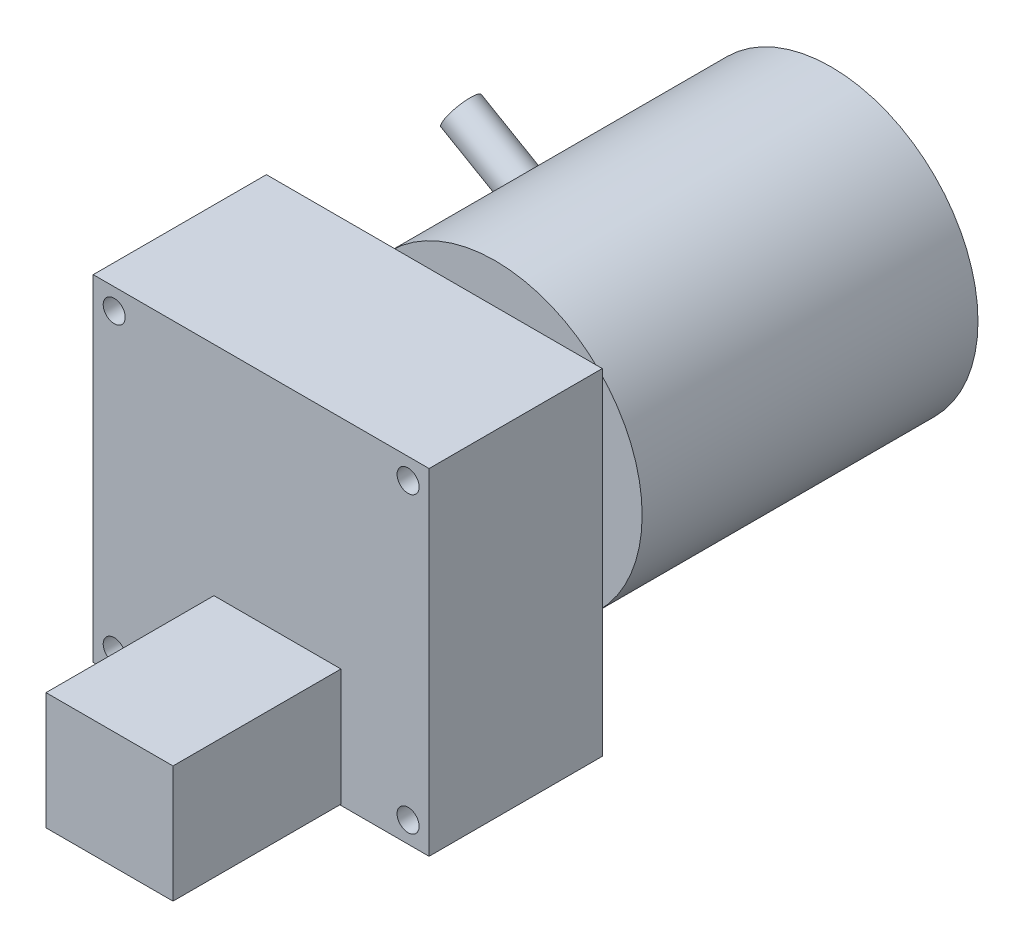
SolidWorks part; units mm, degrees
ref_plane "Front" through (0, 0, 0) normal (0, 0, 1) x (1, 0, 0)
ref_plane "Top" through (0, 0, 0) normal (0, 1, 0) x (1, 0, 0)
ref_plane "Right" through (0, 0, 0) normal (1, 0, 0) x (0, 0, -1)
sketch "草图1" plane through (0, 0, 0) normal (0, 0, 1) x (1, 0, 0)
  circle A0 centre (0, 0) radius 14
  dimension "D1" = 28
extrude "凸台-拉伸1" add sketch "草图1" along normal blind 32
sketch "草图2" plane through (0, 0, 32) normal (0, 0, 1) x (1, 0, 0)
  line L1 (6, 5.5) -> (-6, 5.5)
  line L2 (6, 5.5) -> (6, -5.5)
  line L3 (6, -5.5) -> (-6, -5.5)
  line L4 (-6, 5.5) -> (-6, -5.5)
  line L5 (6, 5.5) -> (-6, -5.5) construction
  line L6 (6, -5.5) -> (-6, 5.5) construction
  point P0 (0, 0)
  dimension "D1" = 11
  dimension "D2" = 12
extrude "凸台-拉伸2" add sketch "草图2" along normal blind 5.8
sketch "草图3" plane through (0, 0, 37.8) normal (0, 0, 1) x (1, 0, 0)
  line L1 (16, 16) -> (-16, 16)
  line L2 (16, 16) -> (16, -16)
  line L3 (16, -16) -> (-16, -16)
  line L4 (-16, 16) -> (-16, -16)
  line L5 (16, 16) -> (-16, -16) construction
  line L6 (16, -16) -> (-16, 16) construction
  point P0 (0, 0)
  dimension "D1" = 32
extrude "凸台-拉伸3" add sketch "草图3" along normal blind 16.5
sketch "草图4" plane through (0, 0, 54.3) normal (0, 0, 1) x (1, 0, 0)
  line L1 (16, -16) -> (7.6, -16)
  line L2 (-16, -16) -> (16, -16) construction
  line L3 (7.6, -16) -> (-4.5, -16)
  line L5 (-4.5, -15.9) -> (-4.5, -4.74)
  line L6 (-4.5, -4.74) -> (7.6, -4.74)
  line L7 (7.6, -4.74) -> (7.6, -15.9)
  line L8 (7.6, -15.9) -> (-4.5, -15.9)
  dimension "D1" = 8.4
  dimension "D2" = 12.1
  dimension "D3" = 0.1
  dimension "D4" = 11.16
extrude "凸台-拉伸4" add sketch "草图4" along normal blind 16 contours L8 L7 L6 L5
sketch "草图5" plane through (0, 0, 54.3) normal (0, 0, 1) x (1, 0, 0)
  line L1 (14, 14) -> (-14, 14)
  line L2 (14, 14) -> (14, -14)
  line L3 (14, -14) -> (-14, -14)
  line L4 (-14, 14) -> (-14, -14)
  line L5 (14, 14) -> (-14, -14) construction
  line L6 (14, -14) -> (-14, 14) construction
  circle A0 centre (-14, 14) radius 1.05
  circle A1 centre (14, 14) radius 1.05
  circle A2 centre (-14, -14) radius 1.05
  circle A3 centre (14, -14) radius 1.05
  point P0 (0, 0)
  dimension "D2" = 2.1
  dimension "D3" = 2.1
  dimension "D4" = 2.1
  dimension "D5" = 2.1
  dimension "D1" = 28
extrude "切除-拉伸1" cut sketch "草图5" against normal up to surface (16.5 mm away) contours A1 | A0 | A2 | A3 up to face at (0, 0, 37.8)
ref_plane "基准面1" through (-18.9282, 10.9282, 0) normal (-0.866, 0.5, 0) x (0, 0, -1)
sketch "草图6" plane through (-18.9282, 10.9282, 0) normal (-0.866, 0.5, 0) x (0, 0, -1)
  line L0 (-32, 14) -> (-32, -14)
  line L1 (-32, 0) -> (-17.5, 0)
  circle A0 centre (-17.5, 0) radius 1.75
  dimension "D2" = 3.5
  dimension "D1" = 14.5
extrude "凸台-拉伸6" add sketch "草图6" along normal blind 20.5 from offset 21.86 contours A0
